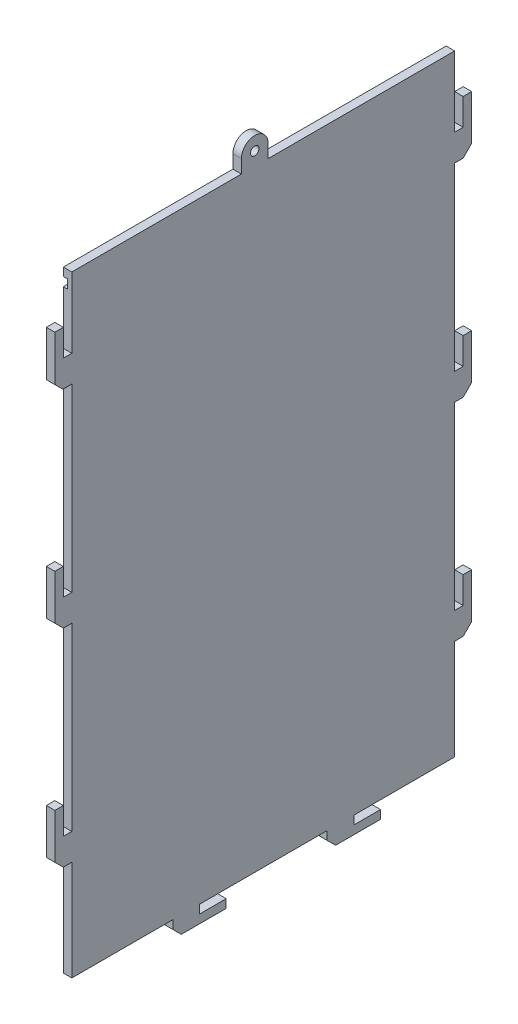
SolidWorks part; units mm, degrees
ref_plane "Front Plane" through (0, 0, 0) normal (0, 0, 1) x (1, 0, 0)
ref_plane "Top Plane" through (0, 0, 0) normal (0, 1, 0) x (1, 0, 0)
ref_plane "Right Plane" through (0, 0, 0) normal (1, 0, 0) x (0, 0, -1)
sketch "Sketch2" plane through (0, 0, 0) normal (1, 0, 0) x (0, 0, -1)
  line L3 (12.0032, 442.0977) -> (138.9532, 442.0977)
  line L4 (311.3032, 375.7477) -> (311.3032, 409.3977)
  line L8 (12.0032, -15.6023) -> (12.0032, 59.3977)
  line L12 (298.6032, -15.6023) -> (298.6032, 59.3977)
  line L17 (12.0032, -15.6023) -> (87.6032, -15.6023)
  line L20 (298.6032, 234.3977) -> (298.6032, 369.3977)
  line L21 (298.6032, 389.3977) -> (304.9532, 389.3977)
  line L22 (304.9532, 389.3977) -> (304.9532, 409.3977)
  line L23 (304.9532, 409.3977) -> (311.3032, 409.3977)
  line L24 (304.9532, 369.3977) -> (298.6032, 369.3977)
  line L25 (304.9532, 214.3977) -> (298.6032, 214.3977)
  line L26 (298.6032, 234.3977) -> (304.9532, 234.3977)
  line L27 (311.3032, 220.7477) -> (311.3032, 254.3977)
  line L28 (304.9532, 234.3977) -> (304.9532, 254.3977)
  line L29 (304.9532, 254.3977) -> (311.3032, 254.3977)
  line L30 (304.9532, 59.3977) -> (298.6032, 59.3977)
  line L31 (298.6032, 79.3977) -> (304.9532, 79.3977)
  line L32 (311.3032, 65.7477) -> (311.3032, 99.3977)
  line L33 (304.9532, 79.3977) -> (304.9532, 99.3977)
  line L34 (304.9532, 99.3977) -> (311.3032, 99.3977)
  line L35 (298.6032, 389.3977) -> (298.6032, 442.0977)
  line L36 (298.6032, 79.3977) -> (298.6032, 214.3977)
  line L37 (12.0032, 214.3661) -> (12.0032, 214.3977)
  line L38 (311.3032, 375.7477) -> (304.9532, 369.3977)
  line L39 (5.6532, 59.3977) -> (12.0032, 59.3977)
  line L40 (-0.6968, 65.7477) -> (-0.6968, 99.3977)
  line L41 (5.6532, 99.3977) -> (-0.6968, 99.3977)
  line L42 (5.6532, 79.3977) -> (5.6532, 99.3977)
  line L43 (12.0032, 79.3977) -> (5.6532, 79.3977)
  line L44 (5.6532, 214.3977) -> (12.0032, 214.3977)
  line L45 (-0.6968, 220.7477) -> (-0.6968, 254.3977)
  line L46 (5.6532, 254.3977) -> (-0.6968, 254.3977)
  line L47 (5.6532, 234.3977) -> (5.6532, 254.3977)
  line L48 (12.0032, 234.3977) -> (5.6532, 234.3977)
  line L49 (5.3132, 369.3977) -> (12.0032, 369.3977)
  line L50 (-0.6968, 375.4078) -> (-0.6968, 409.3977)
  line L51 (5.6532, 409.3977) -> (-0.6968, 409.3977)
  line L52 (5.6532, 389.3977) -> (5.6532, 409.3977)
  line L53 (12.0032, 389.3977) -> (5.6532, 389.3977)
  line L54 (12.0032, 389.3977) -> (12.0032, 442.0977)
  line L55 (12.0032, 234.3977) -> (12.0032, 369.3977)
  line L56 (12.0032, 79.3977) -> (12.0032, 214.3661)
  line L57 (311.3032, 220.7477) -> (304.9532, 214.3977)
  line L58 (311.3032, 65.7477) -> (304.9532, 59.3977)
  line L59 (5.6532, 59.3977) -> (-0.6968, 65.7477)
  line L60 (5.6532, 214.3977) -> (-0.6968, 220.7477)
  line L61 (5.3132, 369.3977) -> (-0.6968, 375.4078)
  line L62 (223.1032, -21.9523) -> (243.1032, -21.9523)
  line L63 (203.1032, -21.9523) -> (203.1032, -15.6023)
  line L64 (209.4532, -28.3023) -> (203.1032, -21.9523)
  line L65 (223.1032, -15.6023) -> (223.1032, -21.9523)
  line L66 (209.4532, -28.3023) -> (243.1032, -28.3023)
  line L67 (243.1032, -21.9523) -> (243.1032, -28.3023)
  line L68 (87.6032, -21.9523) -> (87.6032, -15.6023)
  line L69 (93.9532, -28.3023) -> (87.6032, -21.9523)
  line L70 (93.9532, -28.3023) -> (127.6032, -28.3023)
  line L71 (127.6032, -21.9523) -> (127.6032, -28.3023)
  line L72 (107.6032, -21.9523) -> (127.6032, -21.9523)
  line L73 (107.6032, -15.6023) -> (107.6032, -21.9523)
  line L74 (223.1032, -15.6023) -> (298.6032, -15.6023)
  line L75 (107.6032, -15.6023) -> (203.1032, -15.6023)
  line L76 (138.9532, 452.0977) -> (138.9532, 442.0977)
  line L77 (158.9532, 452.0977) -> (158.9532, 442.0977)
  line L78 (158.9532, 442.0977) -> (298.6032, 442.0977)
  arc A0 (158.9532, 452.0977) -> (138.9532, 452.0977) centre (148.9532, 452.0977) ccw
  circle A1 centre (148.9532, 452.0977) radius 3.175
  point P2 (2.4782, 99.3977)
  point P19 (8.8282, 59.3977)
  dimension "D41" = 20
  dimension "D42" = 126.95
  dimension "D2" = 6.35
  dimension "D3" = 6.35
  dimension "D4" = 6.35
  dimension "D5" = 6.35
  dimension "D6" = 3
  dimension "D7" = 286.6
  dimension "D8" = 40
  dimension "D9" = 6.35
  dimension "D10" = 40
  dimension "D11" = 20
  dimension "D12" = 6.35
  dimension "D13" = 6.35
  dimension "D14" = 6.35
  dimension "D15" = 6.35
  dimension "D16" = 6.35
  dimension "D17" = 6.35
  dimension "D18" = 6.35
  dimension "D19" = 20
  dimension "D20" = 40
  dimension "D21" = 20
  dimension "D22" = 20
  dimension "D23" = 40
  dimension "D24" = 6.35
  dimension "D25" = 6.35
  dimension "D26" = 6.35
  dimension "D27" = 6.35
  dimension "D28" = 6.35
  dimension "D29" = 155
  dimension "D30" = 155
  dimension "D31" = 52.7
  dimension "D32" = 52.7
  dimension "D33" = 457.7
  dimension "D34" = 155
  dimension "D35" = 2
  dimension "D36" = 95.5
  dimension "D37" = 95.5
  dimension "D38" = 6.35
  dimension "D39" = 6.35
  dimension "D40" = 6.35
extrude "Boss-Extrude1" add sketch "Sketch2" along normal blind 6.35
sketch "Sketch3" plane through (0, 0, -12.0032) normal (0, 0, 1) x (1, 0, 0)
  line L0 (0, 442.0977) -> (0, 389.3977) construction
  line L1 (0, 436.0017) -> (3.175, 436.0017)
  line L2 (0, 436.0017) -> (0, 429.3977)
  line L3 (0, 429.3977) -> (3.175, 429.3977)
  line L4 (3.175, 436.0017) -> (3.175, 429.3977)
  line L5 (6.35, 442.0977) -> (0, 442.0977) construction
  dimension "D1" = 6.096
  dimension "D2" = 6.604
  dimension "D3" = 3.175
extrude "Cut-Extrude1" cut sketch "Sketch3" against normal through all
